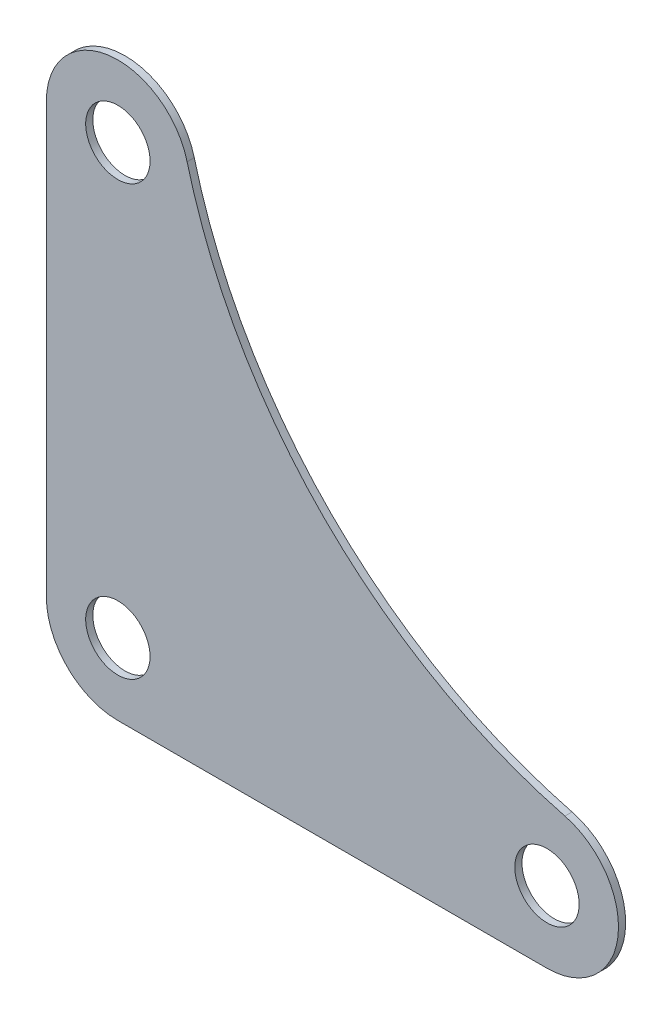
SolidWorks part; units mm, degrees
ref_plane "Front Plane" through (0, 0, 0) normal (0, 0, 1) x (1, 0, 0)
ref_plane "Top Plane" through (0, 0, 0) normal (0, 1, 0) x (1, 0, 0)
ref_plane "Right Plane" through (0, 0, 0) normal (1, 0, 0) x (0, 0, -1)
sketch "Sketch1" plane through (0, 0, 0) normal (0, 0, 1) x (1, 0, 0)
  line L0 (0, 0) -> (70, 0)
  line L1 (0, 0) -> (0, 70)
  line L2 (80, 10) -> (0, 10) construction
  line L3 (10, 80) -> (10, 0) construction
  line L4 (90.9208, 90.9208) -> (38.8909, 38.8909) construction
  arc A0 (70, 0) -> (72.503, 19.6817) centre (70, 10) ccw
  arc A1 (19.6817, 72.503) -> (0, 70) centre (10, 70) ccw
  arc A2 (19.6817, 72.503) -> (72.503, 19.6817) centre (90.9208, 90.9208) ccw
  point P6 (80, 10)
  dimension "D3" = 20
  dimension "D1" = 80
  dimension "D2" = 55
extrude "Boss-Extrude1" add sketch "Sketch1" along normal blind 1
fillet "Fillet1" radius 10 1 edges at (0, 0, 0.5)
sketch "Sketch2" plane through (0, 0, 1) normal (0, 0, 1) x (1, 0, 0)
  circle A0 centre (10, 10) radius 4.5
  circle A1 centre (70, 10) radius 4.5
  circle A2 centre (10, 70) radius 4.5
  dimension "D1" = 9
extrude "Cut-Extrude1" cut sketch "Sketch2" against normal blind 10
